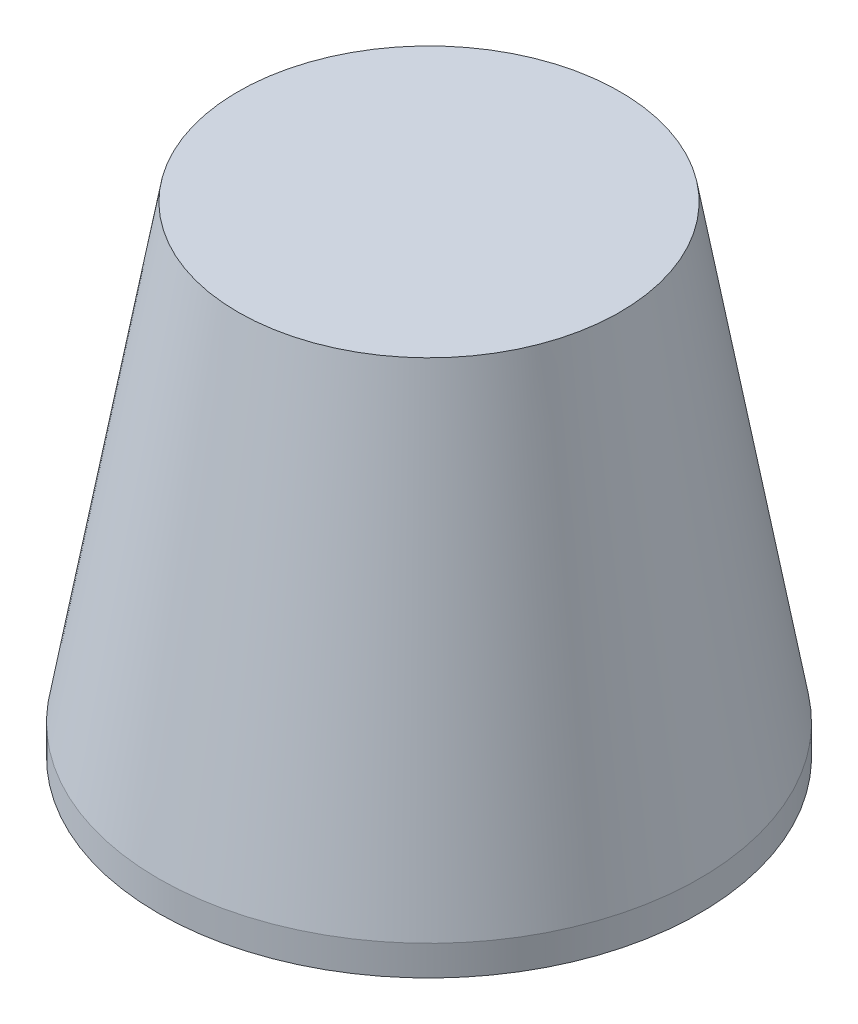
SolidWorks part; units mm, degrees
ref_plane "前视基准面" through (0, 0, 0) normal (0, 0, 1) x (1, 0, 0)
ref_plane "上视基准面" through (0, 0, 0) normal (0, 1, 0) x (1, 0, 0)
ref_plane "右视基准面" through (0, 0, 0) normal (1, 0, 0) x (0, 0, -1)
sketch "草图1" plane through (0, 0, 0) normal (0, 1, 0) x (1, 0, 0)
  circle A0 centre (0, 0) radius 9
  dimension "D1" = 18
extrude "凸台-拉伸1" add sketch "草图1" along normal blind 10 and the other way blind 6
chamfer "倒角1" distance 15 angle 10 1 edges at (0, 10, 9)
